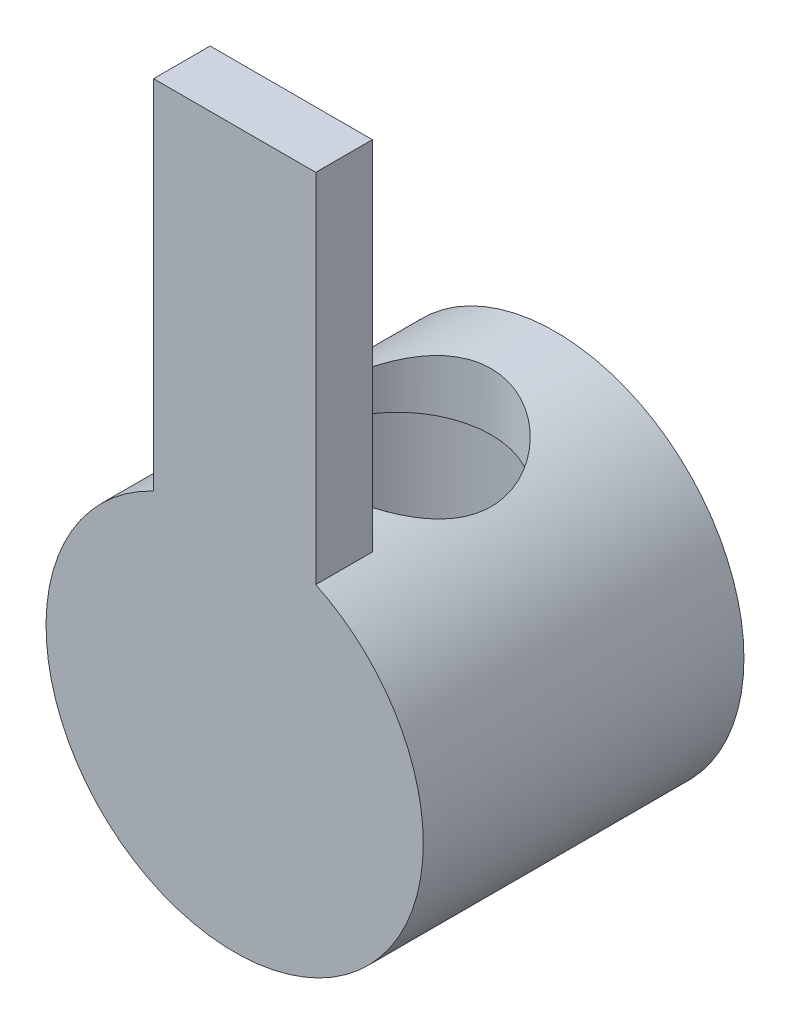
SolidWorks part; units mm, degrees
ref_plane "前视基准面" through (0, 0, 0) normal (0, 0, 1) x (1, 0, 0)
ref_plane "上视基准面" through (0, 0, 0) normal (0, 1, 0) x (1, 0, 0)
ref_plane "右视基准面" through (0, 0, 0) normal (1, 0, 0) x (0, 0, -1)
sketch "草图1" plane through (0, 0, 0) normal (0, 0, 1) x (1, 0, 0)
  line L1 (-2.15, -9) -> (2.15, -9)
  line L2 (-2.15, -9) -> (-2.15, 9)
  line L3 (-2.15, 9) -> (2.15, 9)
  line L4 (2.15, -9) -> (2.15, 9)
  line L5 (-2.15, -9) -> (2.15, 9) construction
  line L6 (-2.15, 9) -> (2.15, -9) construction
  point P0 (0, 0)
  dimension "D1" = 4.3
  dimension "D2" = 18
extrude "凸台-拉伸1" add sketch "草图1" along normal blind 1.5
sketch "草图4" plane through (0, 0, 0) normal (0, 0, -1) x (-1, 0, 0)
  line L0 (2.15, 9) -> (2.15, -9) construction
  line L1 (-2.15, -9) -> (2.15, -9)
  line L2 (-2.15, -9) -> (-2.15, -7.0516)
  line L3 (-2.15, -7.0516) -> (2.15, -7.0516)
  line L4 (2.15, -9) -> (2.15, -7.0516)
extrude "切除-拉伸1" cut sketch "草图4" against normal through all
sketch "草图2" plane through (0, 0, 1.5) normal (0, 0, 1) x (1, 0, 0)
  circle A0 centre (0, -4.98) radius 5
  dimension "D1" = 10
extrude "凸台-拉伸2" add sketch "草图2" against normal blind 8.5
sketch "草图5" plane through (0, 9, 0) normal (0, 1, 0) x (1, 0, 0)
  line L0 (0, -1.5) -> (0, 7) construction
  line L1 (2.15, -1.5) -> (-2.15, -1.5) construction
  line L2 (5, 7) -> (-5, 7) construction
  circle A0 centre (0, 2.8) radius 2.5
  dimension "D1" = 5
  dimension "D2" = 4.3
extrude "切除-拉伸2" cut sketch "草图5" against normal through all
ref_plane "基准面1" through (0, -14.23, 0) normal (0, 1, 0) x (-1, 0, 0)
ref_plane "基准面2" through (0, -4, 0) normal (0, 1, 0) x (1, 0, 0)
sketch "草图6" plane through (0, -4, 0) normal (0, 1, 0) x (1, 0, 0)
  circle A0 centre (0, 2.8) radius 3.5
extrude "切除-拉伸3" cut sketch "草图6" against normal blind 10 and the other way blind 2.5
